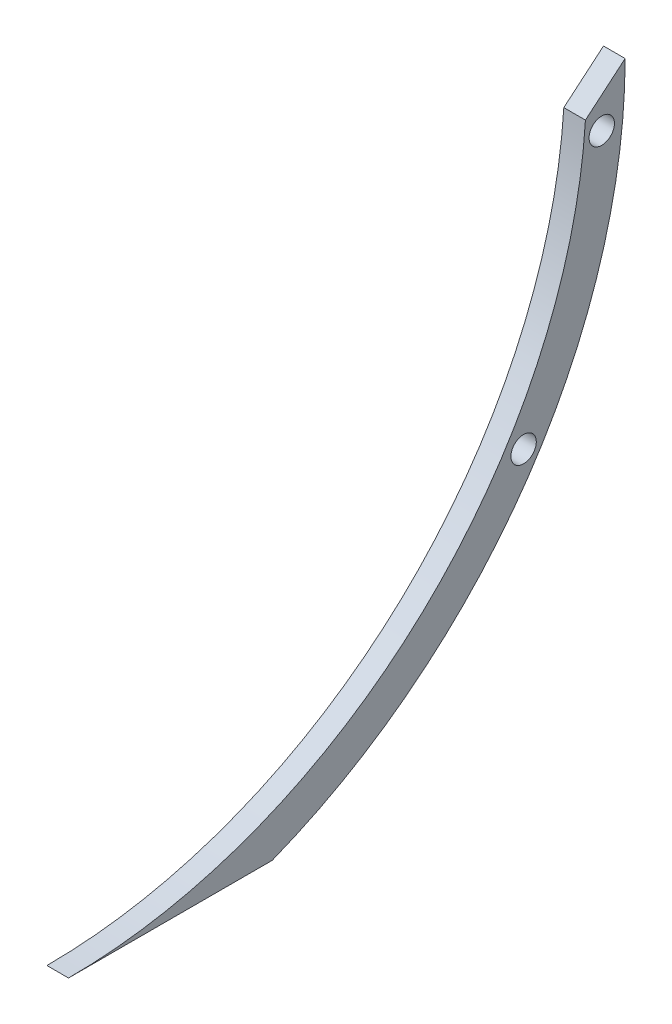
SolidWorks part; units mm, degrees
ref_plane "Front Plane" through (0, 0, 0) normal (0, 0, 1) x (1, 0, 0)
ref_plane "Top Plane" through (0, 0, 0) normal (0, 1, 0) x (1, 0, 0)
ref_plane "Right Plane" through (0, 0, 0) normal (1, 0, 0) x (0, 0, -1)
sketch "Sketch1" plane through (0, 0, 0) normal (1, 0, 0) x (0, 0, -1)
  line L0 (0, 0) -> (0, -139.192)
  line L1 (0, 0) -> (139.192, 0)
  line L2 (0, 0) -> (113.8047, -71.9099)
  line L3 (0, -129.54) -> (91.3565, -129.54)
  line L5 (129.54, 0) -> (139.192, 0)
  circle A0 centre (0, 0) radius 129.54
  circle A1 centre (0, 0) radius 139.192
  circle A2 centre (133.35, -12.7) radius 3.175
  circle A3 centre (113.8047, -71.9099) radius 3.175
  dimension "D1" = 9.652
  dimension "D4" = 134.62
  dimension "D2" = 12.7
  dimension "D3" = 133.35
extrude "Boss-Extrude2" add sketch "Sketch1" along normal blind 5.4102
sketch "Sketch2" plane through (5.4102, 0, 0) normal (1, 0, 0) x (0, 0, -1)
  line L0 (139.192, 0) -> (129.2688, -8.3778)
  line L1 (129.2688, -8.3778) -> (129.54, 0)
  line L2 (129.54, 0) -> (139.192, 0)
  arc A0 (0, -129.54) -> (129.54, 0) centre (0, 0) ccw construction
extrude "Cut-Extrude1" cut sketch "Sketch2" against normal blind 5.4102
